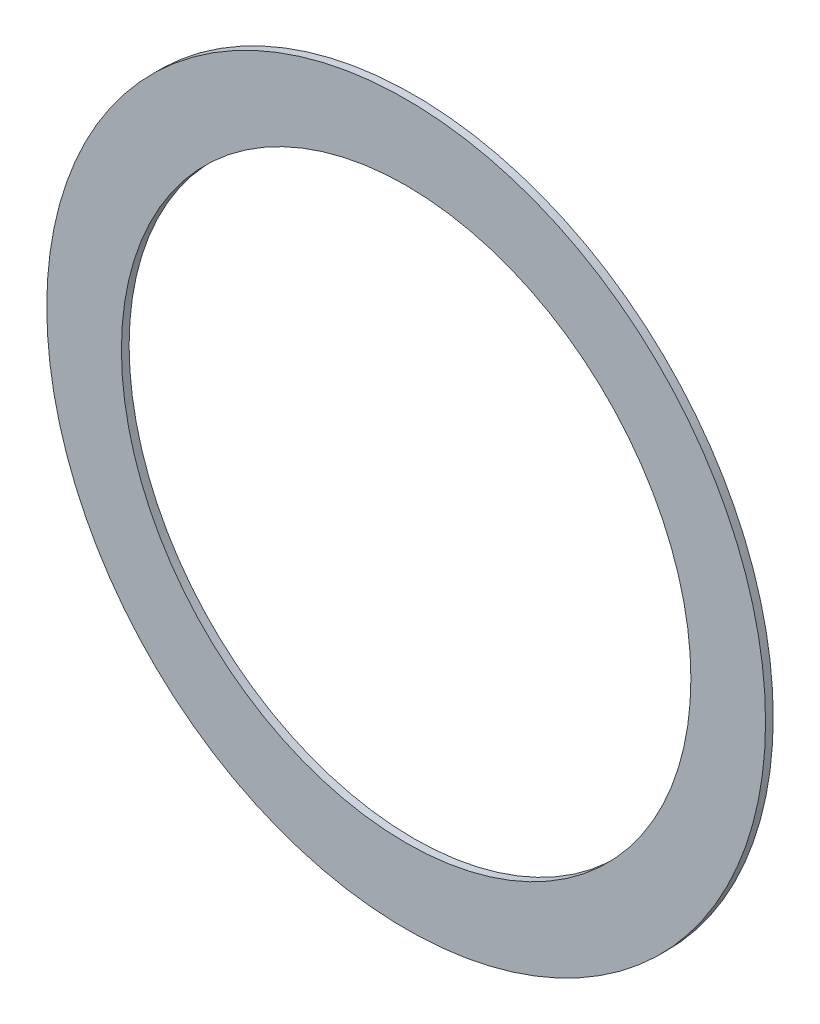
SolidWorks part; units mm, degrees
ref_plane "Plan1" through (0, 0, 0) normal (0, 0, 1) x (1, 0, 0)
ref_plane "Plan2" through (0, 0, 0) normal (0, 1, 0) x (1, 0, 0)
ref_plane "Plan3" through (0, 0, 0) normal (1, 0, 0) x (0, 0, -1)
sketch "Esquisse1" plane through (0, 0, 0) normal (0, 0, 1) x (1, 0, 0)
  circle A0 centre (0, 0) radius 18.5
  circle A1 centre (0, 0) radius 23.35
  dimension "D1" = 37
  dimension "D2" = 46.7
extrude "Base-Extrusion" add sketch "Esquisse1" along normal blind 0.5
